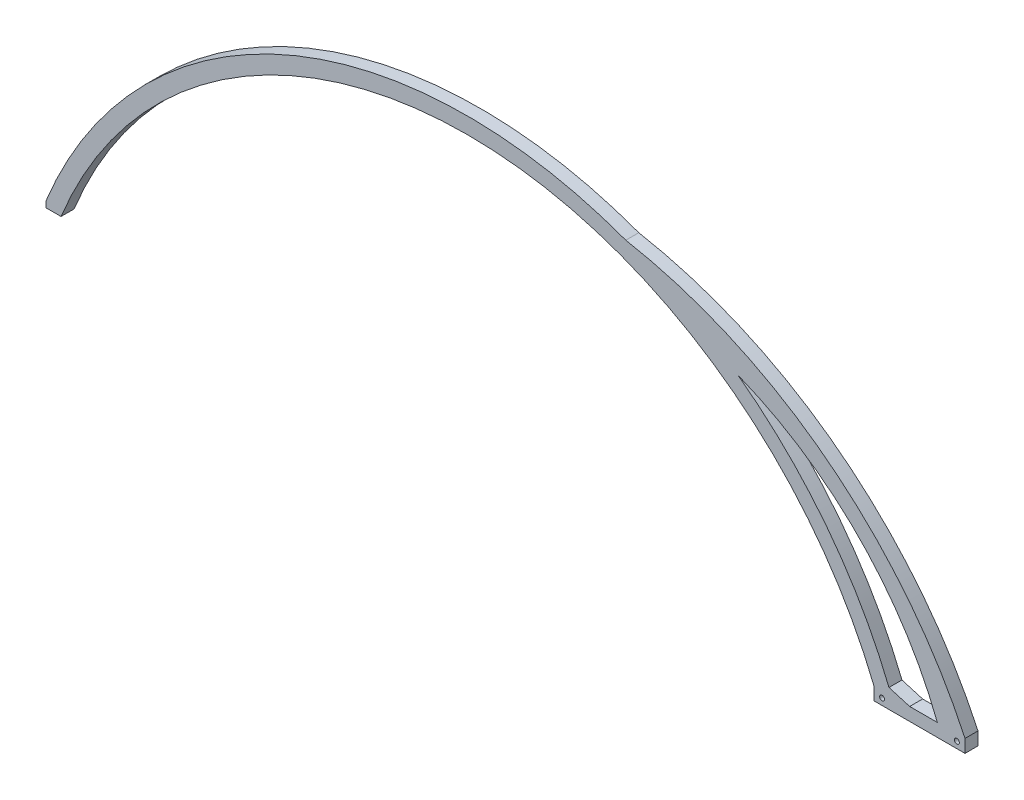
SolidWorks part; units mm, degrees
ref_plane "前视基准面" through (0, 0, 0) normal (0, 0, 1) x (1, 0, 0)
ref_plane "上视基准面" through (0, 0, 0) normal (0, 1, 0) x (1, 0, 0)
ref_plane "右视基准面" through (0, 0, 0) normal (1, 0, 0) x (0, 0, -1)
sketch "草图1" plane through (0, 0, 0) normal (0, 0, 1) x (1, 0, 0)
  line L0 (0, -4) -> (5, -4) construction
  line L1 (0, 0) -> (56.1, 0)
  line L2 (0, 0) -> (0, -8)
  line L3 (0, -8) -> (56.1, -8)
  line L4 (56.1, 0) -> (56.1, -8)
  line L9 (28.05, 0) -> (28.05, -24.8781) construction
  circle A0 centre (5, -4) radius 1.5
  circle A1 centre (51.1, -4) radius 1.5
  dimension "D3" = 3
  dimension "D1" = 8
  dimension "D2" = 5
  dimension "D4" = 46.1
extrude "凸台-拉伸1" add sketch "草图1" along normal blind 8
sketch "草图3" plane through (0, 0, 0) normal (0, 0, -1) x (-1, 0, 0)
  line L0 (-9.2711, 3.7478) -> (-22.0146, 0)
  line L1 (-56.1, 0) -> (0, 0) construction
  line L2 (-22.0146, 0) -> (0, 0)
  line L3 (500.6414, 0) -> (509.9125, 0)
  line L4 (509.9125, 0) -> (509.9125, 3.7478)
  line L5 (-56.1, 0) -> (-43.9198, 0)
  line L6 (96.9282, 133.0544) -> (101.3629, 124.0915)
  arc A0 (0, 0) -> (500.6414, 0) centre (250.3207, -101.1907) cw
  arc A1 (-9.2711, 3.7478) -> (509.9125, 3.7478) centre (250.3207, -101.1907) cw
  arc A2 (-56.1, 0) -> (96.9282, 133.0544) centre (274.3526, -225.532) cw
  arc A3 (-47.8403, -5.6372) -> (101.3629, 124.0915) centre (274.3526, -225.532) cw
  dimension "D1" = 270
  dimension "D2" = 640.7837
  dimension "D3" = 10
  dimension "D4" = 10
extrude "凸台-拉伸5" add sketch "草图3" against normal blind 8 contours L4 A1 L0 L2 A0 L3
sketch "草图4" plane through (0, 0, 0) normal (0, 0, -1) x (-1, 0, 0)
  line L0 (-56.1, 0) -> (-39.0573, 0)
  line L7 (0, -8) -> (0, 0)
  line L8 (500.6414, 0) -> (509.9125, 0)
  line L9 (509.9125, 0) -> (509.9125, 3.7478)
  line L10 (-9.2711, 3.7478) -> (-22.0146, 0)
  line L11 (-22.0146, 0) -> (-56.1, 0)
  line L12 (-56.1, 0) -> (-56.1, -8)
  line L13 (-56.1, -8) -> (0, -8)
  line L14 (0, -8) -> (0, 0)
  line L15 (500.6414, 0) -> (509.9125, 0)
  line L16 (509.9125, 0) -> (509.9125, 3.7478)
  line L17 (-9.2711, 3.7478) -> (-22.0146, 0)
  line L18 (-22.0146, 0) -> (-56.1, 0)
  line L19 (-56.1, 0) -> (-56.1, -8)
  line L20 (-56.1, -8) -> (0, -8)
  arc A0 (-56.1, 0) -> (152.8082, 161.2809) centre (204.4465, -121.5471) cw
  arc A1 (-39.0573, 0) -> (83.7273, 123.8574) centre (164.1132, -78.6215) cw
  arc A2 (500.6414, 0) -> (0, 0) centre (250.3207, -101.1907) ccw
  arc A3 (509.9125, 3.7478) -> (-9.2711, 3.7478) centre (250.3207, -101.1907) ccw
  arc A4 (500.6414, 0) -> (0, 0) centre (250.3207, -101.1907) ccw
  arc A5 (509.9125, 3.7478) -> (-9.2711, 3.7478) centre (250.3207, -101.1907) ccw
  arc M14 (509.9125, 3.7478) -> (-9.2711, 3.7478) centre (250.3207, -101.1907) ccw
  line M16 (-22.0146, 0) -> (-56.1, 0)
  dimension "D1" = 0
extrude "凸台-拉伸6" add sketch "草图4" against normal blind 8 contours A1 A0 M16 M14
